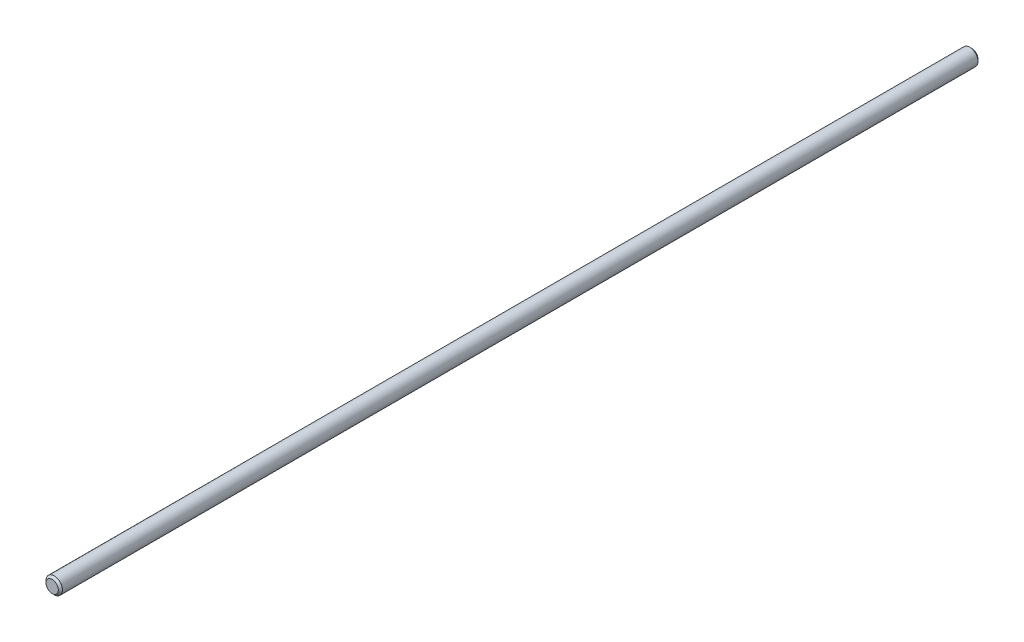
SolidWorks part; units mm, degrees
ref_plane "Piano frontale" through (0, 0, 0) normal (0, 0, 1) x (1, 0, 0)
ref_plane "Piano superiore" through (0, 0, 0) normal (0, 1, 0) x (1, 0, 0)
ref_plane "Piano destro" through (0, 0, 0) normal (1, 0, 0) x (0, 0, -1)
sketch "Schizzo1" plane through (0, 0, 0) normal (0, 0, 1) x (1, 0, 0)
  circle A0 centre (0, 0) radius 4
  dimension "D1" = 8
extrude "Estrusione-Estrusione1" add sketch "Schizzo1" along normal blind 448
chamfer "Smusso1" distance 1 angle 45 2 edges at (4, 0, 448) (4, 0, 0)
sketch "Schizzo2" plane through (0, 0, 0) normal (0, 1, 0) x (1, 0, 0)
  line L0 (4, -447) -> (4, -1) construction
  line L1 (4, -447) -> (4, -1) construction
  line L2 (4, -447) -> (-4, -447) construction
  line L3 (4, -1) -> (-4, -1) construction
